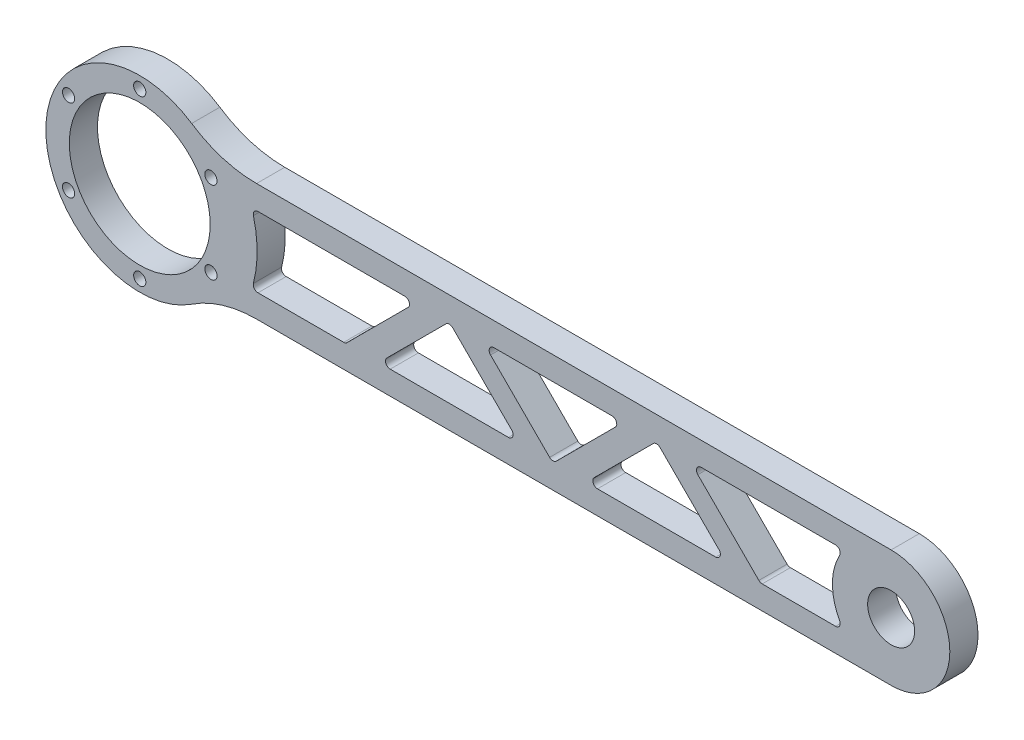
SolidWorks part; units mm, degrees
material "环氧树脂FR-4"
ref_plane "前视基准面" through (0, 0, 0) normal (0, 0, 1) x (1, 0, 0)
ref_plane "上视基准面" through (0, 0, 0) normal (0, 1, 0) x (1, 0, 0)
ref_plane "右视基准面" through (0, 0, 0) normal (1, 0, 0) x (0, 0, -1)
sketch "草图1" plane through (0, 0, 0) normal (0, 0, 1) x (1, 0, 0)
  line L0 (0, 0) -> (320, 0) construction
  line L3 (320, 25) -> (49.7494, 25)
  line L4 (320, -25) -> (49.7494, -25)
  arc A2 (22.1108, 33.3333) -> (22.1108, -33.3333) centre (0, 0) ccw
  arc A3 (320, -25) -> (320, 25) centre (320, 0) ccw
  arc A4 (49.7494, -25) -> (22.1108, -33.3333) centre (49.7494, -75) ccw
  arc A5 (49.7494, 25) -> (22.1108, 33.3333) centre (49.7494, 75) cw
  dimension "D1" = 80
  dimension "D3" = 50
  dimension "D4" = 50
  dimension "D2" = 320
extrude "凸台-拉伸1" add sketch "草图1" along normal blind 12
sketch "草图4" plane through (0, 0, 12) normal (0, 0, 1) x (1, 0, 0)
  circle A0 centre (0, 0) radius 35 construction
  point P3 (0, 35)
  point P6 (30.3109, 17.5)
  point P7 (30.3109, -17.5)
  point P8 (0, -35)
  point P9 (-30.3109, -17.5)
  point P10 (-30.3109, 17.5)
  dimension "D1" = 70
  dimension "D2" = 6
sketch "草图5" plane through (0, 0, 12) normal (0, 0, 1) x (1, 0, 0)
  circle A0 centre (0, 0) radius 30
  circle A1 centre (320, 0) radius 10
  dimension "D1" = 60
  dimension "D2" = 20
extrude "切除-拉伸1" cut sketch "草图5" against normal through all
sketch "草图6" plane through (0, 0, 12) normal (0, 0, 1) x (1, 0, 0)
  line L0 (47.697, 15) -> (117.697, 15)
  line L1 (117.697, 15) -> (87.697, -15)
  line L2 (87.697, -15) -> (47.697, -15)
  line L3 (320, 25) -> (49.7494, 25) construction
  line L4 (49.7494, -25) -> (320, -25) construction
  line L5 (131.8391, 15) -> (101.8391, -15)
  line L6 (101.8391, -15) -> (161.8391, -15)
  line L7 (161.8391, -15) -> (131.8391, 15)
  line L8 (145.9812, 15) -> (175.9812, -15)
  line L9 (175.9812, -15) -> (205.9812, 15)
  line L10 (205.9812, 15) -> (145.9812, 15)
  line L11 (220.1234, 15) -> (190.1234, -15)
  line L12 (190.1234, -15) -> (250.1234, -15)
  line L13 (250.1234, -15) -> (220.1234, 15)
  line L14 (234.2655, 15) -> (264.2655, -15)
  line L15 (264.2655, -15) -> (300, -15)
  line L16 (234.2655, 15) -> (300, 15)
  arc A0 (47.697, -15) -> (47.697, 15) centre (0, 0) ccw
  arc A1 (300, 15) -> (300, -15) centre (320, 0) ccw
  dimension "D1" = 100
  dimension "D2" = 10
  dimension "D3" = 10
  dimension "D4" = 40
  dimension "D5" = 70
  dimension "D6" = 10
  dimension "D7" = 10
  dimension "D8" = 10
  dimension "D9" = 10
  dimension "D10" = 0
  dimension "D11" = 10
  dimension "D12" = 60
  dimension "D13" = 10
  dimension "D14" = 10
  dimension "D15" = 10
  dimension "D16" = 10
  dimension "D17" = 10
  dimension "D18" = 10
  dimension "D19" = 60
extrude "切除-拉伸3" cut sketch "草图6" against normal through all
fillet "圆角1" radius 2 17 edges at (300, 15, 6) (234.2655, 15, 6) (300, -15, 6) (264.2655, -15, 6) (190.1234, -15, 6) (250.1234, -15, 6) (220.1234, 15, 6) (205.9812, 15, 6) (145.9812, 15, 6) (175.9812, -15, 6) (161.8391, -15, 6) (101.8391, -15, 6) (131.8391, 15, 6) (117.697, 15, 6) (87.697, -15, 6) (47.697, -15, 6) (47.697, 15, 6)
hole_wizard "Ø5.2 (5.2) 直径孔1" positions "3D草图1" profile "草图7" hole size "Ø5.2" standard "GB" end condition through all
sketch3d "3D草图1"
  point P0 (0, 35, 12)
  point P3 (-30.3109, 17.5, 12)
  point P6 (-30.3109, -17.5, 12)
  point P9 (0, -35, 12)
  point P12 (30.3109, -17.5, 12)
  point P15 (30.3109, 17.5, 12)
sketch "草图7" plane through (0, 35, 12) normal (1, 0, 0) x (0, -1, 0)
  line L0 (0, 0) -> (0, 12)
  line L1 (0, 12) -> (2.6, 12)
  line L2 (2.6, 12) -> (2.6, 0)
  line L5 (2.6, 0) -> (0, 0)
  line L11 (0, -6.35) -> (0, 107.95) construction
  dimension "通孔孔直径" = 5.2
  dimension "通孔孔深度" = 12
